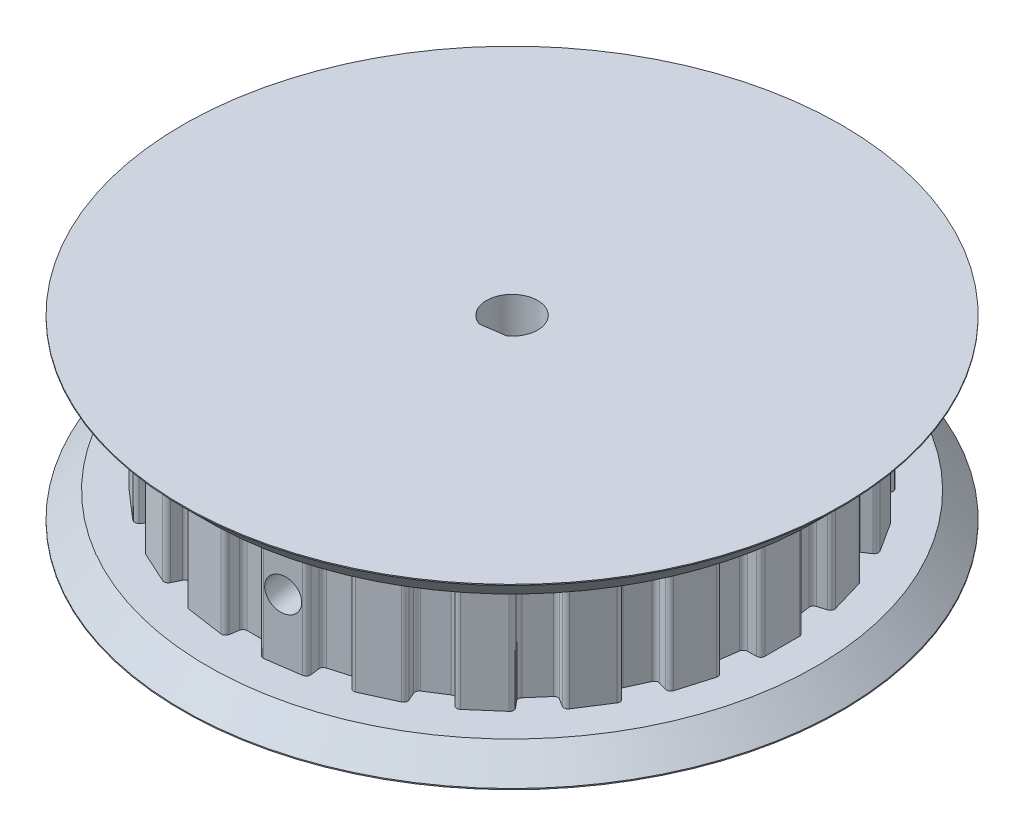
SolidWorks part; units mm, degrees
ref_plane "Front Plane" through (0, 0, 0) normal (0, 0, 1) x (1, 0, 0)
ref_plane "Top Plane" through (0, 0, 0) normal (0, 1, 0) x (1, 0, 0)
ref_plane "Right Plane" through (0, 0, 0) normal (1, 0, 0) x (0, 0, -1)
sketch "Sketch1" plane through (0, 0, 0) normal (0, 1, 0) x (1, 0, 0)
  line L0 (-1.778, 30.8109) -> (1.778, 30.8109) construction
  line L12 (-1.778, 30.8109) -> (-2.0983, 32.8175) construction
  line L13 (1.778, 30.8109) -> (2.0983, 32.8175) construction
  line L14 (2.0983, 32.8175) -> (-2.0983, 32.8175) construction
  line L15 (-2.0983, 32.8175) -> (-7.2325, 32.0793) construction
  line L16 (2.0983, 32.8175) -> (7.2325, 32.0793) construction
  line L17 (7.2325, 32.0793) -> (6.9745, 30.0638) construction
  line L18 (6.9745, 30.0638) -> (10.3864, 29.0619) construction
  line L19 (10.3864, 29.0619) -> (11.2591, 30.897) construction
  line L20 (11.2591, 30.897) -> (7.2325, 32.0793) construction
  line L21 (0, 30.8109) -> (0, 32.8175) construction
  line L22 (8.6804, 29.5629) -> (9.2458, 31.4882) construction
  line L23 (24.8178, 19.0618) -> (25.751, 19.6412)
  line L24 (22.4048, 21.1931) -> (24.1659, 19.1606)
  line L25 (23.1061, 22.6936) -> (22.3997, 21.8524)
  line L26 (19.8857, 26.1459) -> (23.0497, 23.4042)
  line L27 (18.4422, 25.2816) -> (19.1743, 26.1005)
  line L28 (15.5264, 26.6468) -> (17.7888, 25.1928)
  line L29 (15.3358, 27.278) -> (15.7766, 28.2841)
  line L30 (15.5223, 28.9501) -> (11.2591, 30.897) construction
  line L31 (31.1836, 2.6182) -> (32.282, 2.6012)
  line L32 (30.3059, 5.7158) -> (30.6887, 3.0539)
  line L33 (31.7072, 6.599) -> (30.6581, 6.2733)
  line L34 (30.8644, 11.2443) -> (32.0439, 7.2273)
  line L35 (29.1828, 11.2976) -> (30.2415, 11.5907)
  line L36 (27.468, 14.0225) -> (28.5852, 11.5762)
  line L37 (27.6489, 14.6565) -> (28.5637, 15.2646)
  line L38 (28.7098, 15.9623) -> (26.4463, 19.4843)
  line L39 (27.6489, -14.6565) -> (28.5637, -15.2646)
  line L40 (28.5852, -11.5762) -> (27.468, -14.0225)
  line L41 (30.2415, -11.5907) -> (29.1828, -11.2976)
  line L42 (32.0439, -7.2273) -> (30.8644, -11.2443)
  line L43 (30.6581, -6.2733) -> (31.7072, -6.599)
  line L44 (30.6887, -3.0539) -> (30.3059, -5.7158)
  line L45 (31.1836, -2.6182) -> (32.282, -2.6012)
  line L46 (32.7821, -2.0933) -> (32.7821, 2.0933)
  line L47 (15.3358, -27.278) -> (15.7766, -28.2841)
  line L48 (17.7888, -25.1928) -> (15.5264, -26.6468)
  line L49 (19.1743, -26.1005) -> (18.4422, -25.2816)
  line L50 (23.0497, -23.4042) -> (19.8857, -26.1459)
  line L51 (22.3997, -21.8524) -> (23.1061, -22.6936)
  line L52 (24.1659, -19.1606) -> (22.4048, -21.1931)
  line L53 (24.8178, -19.0618) -> (25.751, -19.6412)
  line L54 (26.4463, -19.4843) -> (28.7098, -15.9623)
  line L55 (-1.8463, -31.2388) -> (-2.0194, -32.3236)
  line L56 (1.3447, -30.8109) -> (-1.3447, -30.8109)
  line L57 (2.0194, -32.3236) -> (1.8463, -31.2388)
  line L58 (6.7374, -32.1505) -> (2.5934, -32.7463)
  line L59 (7.0295, -30.4936) -> (7.169, -31.5832)
  line L60 (9.9706, -29.184) -> (7.3903, -29.9417)
  line L61 (10.5725, -29.4533) -> (11.0442, -30.4453)
  line L62 (11.714, -30.6892) -> (15.5223, -28.9501)
  line L63 (-18.4422, -25.2816) -> (-19.1743, -26.1005)
  line L64 (-15.1619, -26.8811) -> (-17.7888, -25.1928)
  line L65 (-15.7766, -28.2841) -> (-15.1619, -26.8811)
  line L66 (-11.714, -30.6892) -> (-15.5223, -28.9501)
  line L67 (-10.5725, -29.4533) -> (-11.0442, -30.4453)
  line L68 (-7.3903, -29.9417) -> (-9.9706, -29.184)
  line L69 (-7.0295, -30.4936) -> (-7.2325, -32.0793)
  line L70 (-7.2325, -32.0793) -> (-2.5934, -32.7463)
  line L71 (-29.1828, -11.2976) -> (-30.2415, -11.5907)
  line L72 (-27.468, -14.0225) -> (-28.5852, -11.5762)
  line L73 (-28.5637, -15.2646) -> (-27.6489, -14.6565)
  line L74 (-26.1759, -19.9051) -> (-28.7098, -15.9623)
  line L75 (-24.8178, -19.0618) -> (-26.1759, -19.9051)
  line L76 (-22.121, -21.5206) -> (-24.1659, -19.1606)
  line L77 (-22.121, -21.5206) -> (-23.4277, -23.0767)
  line L78 (-23.4277, -23.0767) -> (-19.8857, -26.1459)
  line L79 (-30.6581, 6.2733) -> (-31.7072, 6.599)
  line L80 (-30.6887, 3.0539) -> (-30.3059, 5.7158)
  line L81 (-32.282, 2.6012) -> (-31.1836, 2.6182)
  line L82 (-32.7821, -2.0933) -> (-32.7821, 2.0933)
  line L83 (-31.1836, -2.6182) -> (-32.282, -2.6012)
  line L84 (-30.3059, -5.7158) -> (-30.6887, -3.0539)
  line L85 (-30.6581, -6.2733) -> (-31.7072, -6.599)
  line L86 (-32.0439, -7.2273) -> (-30.8644, -11.2443)
  line L87 (-22.3997, 21.8524) -> (-23.1061, 22.6936)
  line L88 (-24.1659, 19.1606) -> (-22.4048, 21.1931)
  line L89 (-25.751, 19.6412) -> (-24.8178, 19.0618)
  line L90 (-28.7098, 15.9623) -> (-26.4463, 19.4843)
  line L91 (-27.6489, 14.6565) -> (-28.5637, 15.2646)
  line L92 (-28.5852, 11.5762) -> (-27.468, 14.0225)
  line L93 (-29.1828, 11.2976) -> (-30.2415, 11.5907)
  line L94 (-30.8644, 11.2443) -> (-32.0439, 7.2273)
  line L95 (-7.0295, 30.4936) -> (-7.2325, 32.0793) construction
  line L96 (-9.9706, 29.184) -> (-7.3903, 29.9417)
  line L97 (-11.0442, 30.4453) -> (-10.5725, 29.4533)
  line L98 (-15.5223, 28.9501) -> (-11.714, 30.6892)
  line L99 (-15.3358, 27.278) -> (-15.7766, 28.2841)
  line L100 (-17.7888, 25.1928) -> (-15.5264, 26.6468)
  line L101 (-18.4422, 25.2816) -> (-19.1743, 26.1005)
  line L102 (-19.8857, 26.1459) -> (-23.0497, 23.4042)
  line L105 (-1.3447, 30.8109) -> (1.3447, 30.8109)
  line L106 (1.8463, 31.2388) -> (2.0194, 32.3236)
  line L107 (2.5934, 32.7463) -> (6.7374, 32.1505)
  line L108 (7.169, 31.5832) -> (7.0295, 30.4936)
  line L109 (7.3903, 29.9417) -> (9.9706, 29.184)
  line L110 (10.5725, 29.4533) -> (11.0442, 30.4453)
  line L111 (11.714, 30.6892) -> (15.5223, 28.9501)
  line L112 (9.2458, 31.4882) -> (9.396, 32) construction
  line L113 (0, 32.8175) -> (0, 33.3509) construction
  line L114 (-7.0295, 30.4936) -> (-7.2325, 32.0793) construction
  line L115 (-7.0295, 30.4936) -> (-7.169, 31.5832)
  line L117 (-6.7374, 32.1505) -> (-2.5934, 32.7463)
  line L118 (-2.0194, 32.3236) -> (-1.8463, 31.2388)
  arc A0 (0, 30.8109) -> (8.6804, 29.5629) centre (0, 0) cw construction
  arc A1 (16.6576, 25.9198) -> (23.2853, 20.1769) centre (0, 0) cw construction
  arc A2 (28.0266, 12.7993) -> (30.4973, 4.3849) centre (0, 0) cw construction
  arc A3 (30.4973, -4.3849) -> (28.0266, -12.7993) centre (0, 0) cw construction
  arc A4 (23.2853, -20.1769) -> (16.6576, -25.9198) centre (0, 0) cw construction
  arc A5 (8.6804, -29.5629) -> (0, -30.8109) centre (0, 0) cw construction
  arc A6 (-8.6804, -29.5629) -> (-16.6576, -25.9198) centre (0, 0) cw construction
  arc A7 (-23.2853, -20.1769) -> (-28.0266, -12.7993) centre (0, 0) cw construction
  arc A8 (-30.4973, -4.3849) -> (-30.4973, 4.3849) centre (0, 0) cw construction
  arc A9 (-28.0266, 12.7993) -> (-23.2853, 20.1769) centre (0, 0) cw construction
  arc A10 (-16.6576, 25.9198) -> (-8.6804, 29.5629) centre (0, 0) cw construction
  arc A12 (-7.3903, 29.9417) -> (-7.0295, 30.4936) centre (-7.5334, 30.4291) ccw
  arc A13 (-10.5725, 29.4533) -> (-9.9706, 29.184) centre (-10.1137, 29.6714) ccw
  arc A14 (-11.714, 30.6892) -> (-11.0442, 30.4453) centre (-11.503, 30.2271) cw
  arc A15 (-30.8644, 11.2443) -> (-30.2415, 11.5907) centre (-30.377, 11.1012) cw
  arc A16 (-29.1828, 11.2976) -> (-28.5852, 11.5762) centre (-29.0473, 11.7872) ccw
  arc A17 (-27.468, 14.0225) -> (-27.6489, 14.6565) centre (-27.9301, 14.2335) ccw
  arc A18 (-28.7098, 15.9623) -> (-28.5637, 15.2646) centre (-28.2824, 15.6877) ccw
  arc A19 (-26.4463, 19.4843) -> (-25.751, 19.6412) centre (-26.019, 19.2097) cw
  arc A20 (-24.8178, 19.0618) -> (-24.1659, 19.1606) centre (-24.5498, 19.4933) ccw
  arc A21 (-23.1061, 22.6936) -> (-23.0497, 23.4042) centre (-22.7171, 23.0203) cw
  arc A22 (-22.3997, 21.8524) -> (-22.4048, 21.1931) centre (-22.7887, 21.5258) cw
  arc A23 (-19.1743, 26.1005) -> (-19.8857, 26.1459) centre (-19.553, 25.762) ccw
  arc A24 (-18.4422, 25.2816) -> (-17.7888, 25.1928) centre (-18.0635, 25.6202) ccw
  arc A25 (-15.3358, 27.278) -> (-15.5264, 26.6468) centre (-15.8011, 27.0741) cw
  arc A26 (-15.7766, 28.2841) -> (-15.5223, 28.9501) centre (-15.3113, 28.488) cw
  arc A27 (-28.7098, -15.9623) -> (-28.5637, -15.2646) centre (-28.2824, -15.6877) cw
  arc A28 (-27.6489, -14.6565) -> (-27.468, -14.0225) centre (-27.9301, -14.2335) ccw
  arc A29 (-28.5852, -11.5762) -> (-29.1828, -11.2976) centre (-29.0473, -11.7872) ccw
  arc A30 (-30.2415, -11.5907) -> (-30.8644, -11.2443) centre (-30.377, -11.1012) cw
  arc A31 (-32.0439, -7.2273) -> (-31.7072, -6.599) centre (-31.5565, -7.0842) cw
  arc A32 (-30.6581, -6.2733) -> (-30.3059, -5.7158) centre (-30.8088, -5.7881) ccw
  arc A33 (-30.6887, -3.0539) -> (-31.1836, -2.6182) centre (-31.1915, -3.1262) ccw
  arc A34 (-32.282, -2.6012) -> (-32.7821, -2.0933) centre (-32.2741, -2.0933) cw
  arc A35 (-32.7821, 2.0933) -> (-32.282, 2.6012) centre (-32.2741, 2.0933) cw
  arc A36 (-31.1836, 2.6182) -> (-30.6887, 3.0539) centre (-31.1915, 3.1262) ccw
  arc A37 (-30.3059, 5.7158) -> (-30.6581, 6.2733) centre (-30.8088, 5.7881) ccw
  arc A38 (-31.7072, 6.599) -> (-32.0439, 7.2273) centre (-31.5565, 7.0842) cw
  arc A39 (-17.7888, -25.1928) -> (-18.4422, -25.2816) centre (-18.0635, -25.6202) ccw
  arc A40 (-19.1743, -26.1005) -> (-19.8857, -26.1459) centre (-19.553, -25.762) cw
  arc A41 (-24.8178, -19.0618) -> (-24.1659, -19.1606) centre (-24.5498, -19.4933) cw
  arc A42 (19.1743, -26.1005) -> (19.8857, -26.1459) centre (19.553, -25.762) ccw
  arc A43 (17.7888, -25.1928) -> (18.4422, -25.2816) centre (18.0635, -25.6202) cw
  arc A44 (15.3358, -27.278) -> (15.5264, -26.6468) centre (15.8011, -27.0741) cw
  arc A45 (15.7766, -28.2841) -> (15.5223, -28.9501) centre (15.3113, -28.488) cw
  arc A46 (11.0442, -30.4453) -> (11.714, -30.6892) centre (11.503, -30.2271) ccw
  arc A47 (9.9706, -29.184) -> (10.5725, -29.4533) centre (10.1137, -29.6714) cw
  arc A48 (7.0295, -30.4936) -> (7.3903, -29.9417) centre (7.5334, -30.4291) cw
  arc A49 (6.7374, -32.1505) -> (7.169, -31.5832) centre (6.6651, -31.6477) ccw
  arc A50 (2.5934, -32.7463) -> (2.0194, -32.3236) centre (2.5211, -32.2435) cw
  arc A51 (1.3447, -30.8109) -> (1.8463, -31.2388) centre (1.3447, -31.3189) cw
  arc A52 (-1.8463, -31.2388) -> (-1.3447, -30.8109) centre (-1.3447, -31.3189) cw
  arc A53 (-2.0194, -32.3236) -> (-2.5934, -32.7463) centre (-2.5211, -32.2435) cw
  arc A54 (-7.3903, -29.9417) -> (-7.0295, -30.4936) centre (-7.5334, -30.4291) cw
  arc A55 (-10.5725, -29.4533) -> (-9.9706, -29.184) centre (-10.1137, -29.6714) cw
  arc A56 (-11.714, -30.6892) -> (-11.0442, -30.4453) centre (-11.503, -30.2271) ccw
  arc A57 (-15.5223, -28.9501) -> (-15.7766, -28.2841) centre (-15.3113, -28.488) cw
  arc A58 (31.1836, 2.6182) -> (30.6887, 3.0539) centre (31.1915, 3.1262) cw
  arc A59 (32.282, 2.6012) -> (32.7821, 2.0933) centre (32.2741, 2.0933) cw
  arc A60 (32.282, -2.6012) -> (32.7821, -2.0933) centre (32.2741, -2.0933) ccw
  arc A61 (30.6887, -3.0539) -> (31.1836, -2.6182) centre (31.1915, -3.1262) cw
  arc A62 (30.6581, -6.2733) -> (30.3059, -5.7158) centre (30.8088, -5.7881) cw
  arc A63 (32.0439, -7.2273) -> (31.7072, -6.599) centre (31.5565, -7.0842) ccw
  arc A64 (30.2415, -11.5907) -> (30.8644, -11.2443) centre (30.377, -11.1012) ccw
  arc A65 (28.5852, -11.5762) -> (29.1828, -11.2976) centre (29.0473, -11.7872) cw
  arc A66 (27.6489, -14.6565) -> (27.468, -14.0225) centre (27.9301, -14.2335) cw
  arc A67 (28.5637, -15.2646) -> (28.7098, -15.9623) centre (28.2824, -15.6877) cw
  arc A68 (25.751, -19.6412) -> (26.4463, -19.4843) centre (26.019, -19.2097) ccw
  arc A69 (24.1659, -19.1606) -> (24.8178, -19.0618) centre (24.5498, -19.4933) cw
  arc A70 (22.3997, -21.8524) -> (22.4048, -21.1931) centre (22.7887, -21.5258) cw
  arc A71 (23.0497, -23.4042) -> (23.1061, -22.6936) centre (22.7171, -23.0203) ccw
  arc A72 (18.4422, 25.2816) -> (17.7888, 25.1928) centre (18.0635, 25.6202) cw
  arc A73 (19.8857, 26.1459) -> (19.1743, 26.1005) centre (19.553, 25.762) ccw
  arc A74 (23.1061, 22.6936) -> (23.0497, 23.4042) centre (22.7171, 23.0203) ccw
  arc A75 (22.4048, 21.1931) -> (22.3997, 21.8524) centre (22.7887, 21.5258) cw
  arc A76 (24.8178, 19.0618) -> (24.1659, 19.1606) centre (24.5498, 19.4933) cw
  arc A77 (25.751, 19.6412) -> (26.4463, 19.4843) centre (26.019, 19.2097) cw
  arc A78 (28.5637, 15.2646) -> (28.7098, 15.9623) centre (28.2824, 15.6877) ccw
  arc A79 (27.468, 14.0225) -> (27.6489, 14.6565) centre (27.9301, 14.2335) cw
  arc A80 (29.1828, 11.2976) -> (28.5852, 11.5762) centre (29.0473, 11.7872) cw
  arc A81 (30.8644, 11.2443) -> (30.2415, 11.5907) centre (30.377, 11.1012) ccw
  arc A82 (31.7072, 6.599) -> (32.0439, 7.2273) centre (31.5565, 7.0842) ccw
  arc A83 (30.3059, 5.7158) -> (30.6581, 6.2733) centre (30.8088, 5.7881) cw
  arc A84 (15.7766, 28.2841) -> (15.5223, 28.9501) centre (15.3113, 28.488) ccw
  arc A85 (15.5264, 26.6468) -> (15.3358, 27.278) centre (15.8011, 27.0741) cw
  arc A86 (11.0442, 30.4453) -> (11.714, 30.6892) centre (11.503, 30.2271) cw
  arc A87 (9.9706, 29.184) -> (10.5725, 29.4533) centre (10.1137, 29.6714) ccw
  arc A88 (7.0295, 30.4936) -> (7.3903, 29.9417) centre (7.5334, 30.4291) ccw
  arc A89 (6.7374, 32.1505) -> (7.169, 31.5832) centre (6.6651, 31.6477) cw
  arc A90 (2.0194, 32.3236) -> (2.5934, 32.7463) centre (2.5211, 32.2435) cw
  arc A91 (1.8463, 31.2388) -> (1.3447, 30.8109) centre (1.3447, 31.3189) cw
  arc A94 (0, 33.3509) -> (9.396, 32) centre (0, 0) cw construction
  arc A95 (-6.7374, 32.1505) -> (-7.169, 31.5832) centre (-6.6651, 31.6477) ccw
  arc A96 (-1.3447, 30.8109) -> (-1.8463, 31.2388) centre (-1.3447, 31.3189) cw
  arc A97 (-2.5934, 32.7463) -> (-2.0194, 32.3236) centre (-2.5211, 32.2435) cw
  dimension "D7" = 0.508
  dimension "D8" = 0.508
  dimension "D9" = 0.508
  dimension "D10" = 0.508
  dimension "D11" = 0.508
  dimension "D12" = 0.508
  dimension "D13" = 0.508
  dimension "D14" = 0.508
  dimension "D6" = 0.508
  dimension "D17" = 0.508
  dimension "D18" = 0.508
  dimension "D1" = 3.556
  dimension "D2" = 2.0066
  dimension "D3" = 2.032
  dimension "D4" = 2.54
  dimension "D15" = 2.54
  dimension "D16" = 9.525
  dimension "D5" = 11
extrude "Boss-Extrude1" add sketch "Sketch1" along normal blind 15.24
sketch "Sketch3" plane through (0, 0, 0) normal (0, 1, 0) x (1, 0, 0)
  circle A0 centre (0, 0) radius 40.005
  dimension "D1" = 80.01
extrude "Boss-Extrude2" add sketch "Sketch3" along normal blind 3.175 from surface at 15.24 starting at face at (0.5489, 15.24, -0.7174)
sketch "Sketch4" plane through (0, 0, 0) normal (0, -1, 0) x (1, 0, 0)
  circle A0 centre (0, 0) radius 40.005
  circle A1 centre (0, 0) radius 40.005 construction
extrude "Boss-Extrude3" add sketch "Sketch4" along normal blind 3.175
chamfer "Chamfer1" distance 3.048 angle 45 1 edges at (0, 15.24, -40.005)
chamfer "Chamfer2" distance 3.048 angle 45 1 edges at (0, 0, -40.005)
sketch "Sketch5" plane through (0, -3.175, 0) normal (0, -1, 0) x (1, 0, 0)
  circle A0 centre (0, 0) radius 3.1115
  dimension "D1" = 6.223
extrude "Cut-Extrude1" cut sketch "Sketch5" against normal through all
ref_plane "Plane3" through (0, 0, 0) normal (0.1423, 0, 0.9898) x (0.9898, 0, -0.1423)
sketch "Sketch11" plane through (0, -3.175, 0) normal (0, -1, 0) x (1, 0, 0)
  line L0 (-1.0881, 2.915) -> (1.8653, 2.4904)
  line L1 (6.0389, -0.8683) -> (-6.0389, 0.8683) construction
  line L2 (-2.3139, -2.8108) -> (0.9518, -3.2803)
  circle A0 centre (0, 0) radius 3.1115 construction
  arc A1 (1.8653, 2.4904) -> (-1.0881, 2.915) centre (0, 0) ccw
  circle M4 centre (0, 0) radius 3.1115
  dimension "D1" = 5.842
extrude "Boss-Extrude4" add sketch "Sketch11" against normal up to surface (21.59 mm away) contours L0 M4
sketch "Sketch10" plane through (0, 0, 0) normal (0.1423, 0, 0.9898) x (0.9898, 0, -0.1423)
  line L0 (0, 18.415) -> (0, -3.175) construction
  line L1 (0, 7.62) -> (0, 18.415)
  line L2 (3.1115, 18.415) -> (-3.1115, 18.415) construction
  line L3 (0, 7.62) -> (0, -3.175)
  line L4 (-40.005, -3.175) -> (40.005, -3.175) construction
  circle A0 centre (0, 7.62) radius 1.9844
  dimension "D1" = 3.9688
extrude "Cut-Extrude3" cut sketch "Sketch10" along normal through all contours A0
ref_plane "Plane4" through (16.6187, 0, -36.3898) normal (0.4154, 0, -0.9096) x (-0.9096, 0, -0.4154)
equation "\"D1@Chamfer1\"=0.12"
equation "\"D1@Chamfer2\"=0.12"
equation "\"D16@Sketch1\"=3/8"
equation "\"D4@Sketch1\"=0.1"
